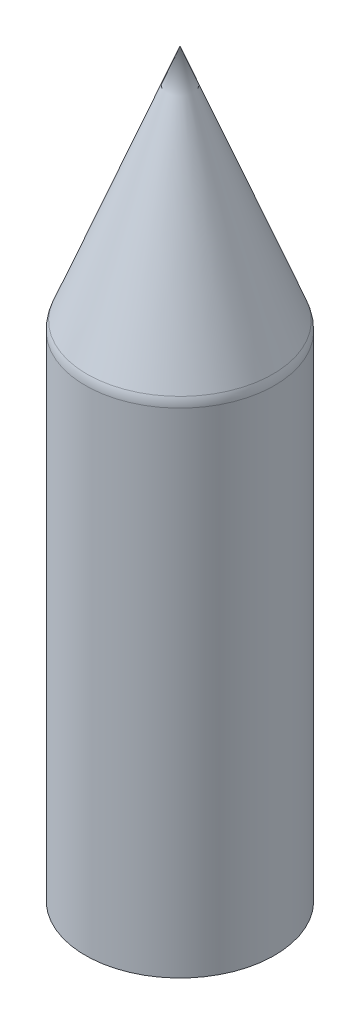
SolidWorks part; units mm, degrees
ref_plane "Płaszczyzna przednia" through (0, 0, 0) normal (0, 0, 1) x (1, 0, 0)
ref_plane "Płaszczyzna górna" through (0, 0, 0) normal (0, 1, 0) x (1, 0, 0)
ref_plane "Płaszczyzna prawa" through (0, 0, 0) normal (1, 0, 0) x (0, 0, -1)
sketch "Szkic1" plane through (0, 0, 0) normal (0, 0, 1) x (1, 0, 0)
  line L0 (0, 0) -> (0, 900)
  line L1 (0, 0) -> (115, 0)
  line L2 (115, 0) -> (115, 600)
  line L3 (112.9431, 610.9172) -> (0, 900)
  arc A0 (115, 600) -> (112.9431, 610.9172) centre (85, 600) ccw
  dimension "D1" = 30
  dimension "D2" = 115
  dimension "D3" = 900
  dimension "D4" = 600
revolve "Obrót1" add sketch "Szkic1" angle 360 about L0
